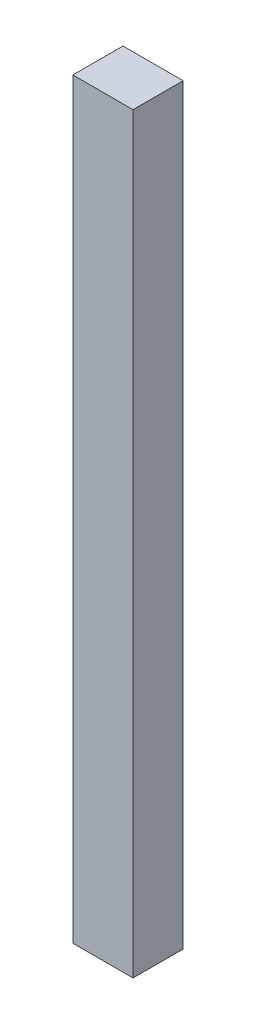
SolidWorks part; units mm, degrees
material "Cast Alloy Steel"
ref_plane "Front Plane" through (0, 0, 0) normal (0, 0, 1) x (1, 0, 0)
ref_plane "Top Plane" through (0, 0, 0) normal (0, 1, 0) x (1, 0, 0)
ref_plane "Right Plane" through (0, 0, 0) normal (1, 0, 0) x (0, 0, -1)
sketch "Sketch1" plane through (0, 0, 0) normal (0, 1, 0) x (1, 0, 0)
  line L1 (-1.524, -1.27) -> (1.524, -1.27)
  line L2 (-1.524, -1.27) -> (-1.524, 1.27)
  line L3 (-1.524, 1.27) -> (1.524, 1.27)
  line L4 (1.524, -1.27) -> (1.524, 1.27)
  line L5 (-1.524, -1.27) -> (1.524, 1.27) construction
  line L6 (-1.524, 1.27) -> (1.524, -1.27) construction
  point P0 (0, 0)
  dimension "D1" = 3.048
  dimension "D2" = 2.54
extrude "Boss-Extrude1" add sketch "Sketch1" along normal blind 38.1
